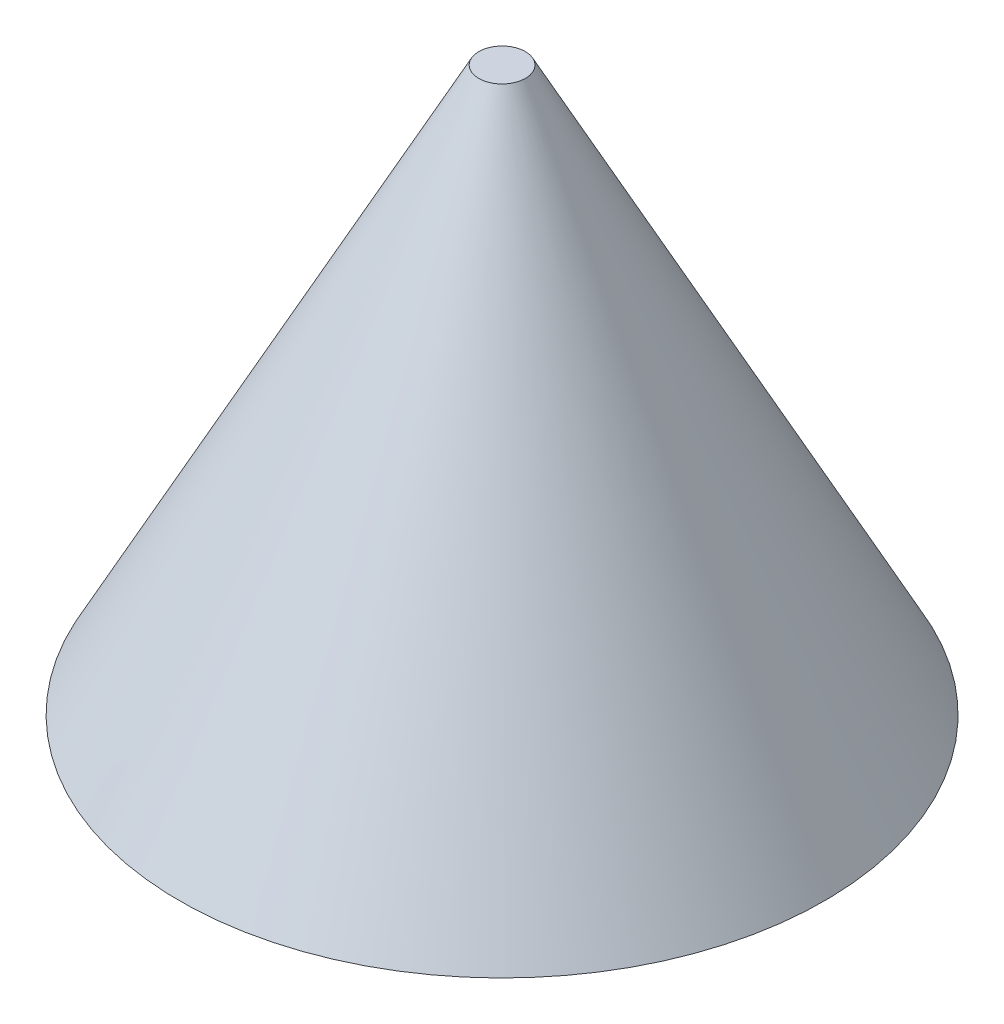
SolidWorks part; units mm, degrees
ref_plane "Plan de face" through (0, 0, 0) normal (0, 0, 1) x (1, 0, 0)
ref_plane "Plan de dessus" through (0, 0, 0) normal (0, 1, 0) x (1, 0, 0)
ref_plane "Plan de droite" through (0, 0, 0) normal (1, 0, 0) x (0, 0, -1)
sketch "Esquisse1" plane through (0, 0, 0) normal (0, 0, 1) x (1, 0, 0)
  line L0 (0, 0) -> (21, 0) construction
  line L1 (21, 0) -> (21, 41.6158)
  line L3 (3, 83.9891) -> (41.5622, 11.4642)
  line L4 (41.5622, 11.4642) -> (37.0319, 11.4642)
  line L5 (37.0319, 11.4642) -> (32.4933, 20)
  line L6 (32.4933, 20) -> (25, 20)
  line L7 (25, 20) -> (25, 0)
  line L8 (25, 0) -> (21, 0)
  line L9 (0, 0) -> (0, 83.9891) construction
  line L10 (3, 83.9891) -> (0, 83.9891)
  line L11 (21, 41.6158) -> (0, 81.111)
  line L12 (0, 83.9891) -> (0, 81.111)
  point P11 (37.1374, 17.0386)
  point P12 (21.4035, 39.2295)
  dimension "D1" = 50
  dimension "D2" = 4
  dimension "D3" = 3
  dimension "D4" = 4
  dimension "D5" = 4
  dimension "D6" = 28
  dimension "D7" = 20
revolve "Révolution1" add sketch "Esquisse1" angle 360 about L9
